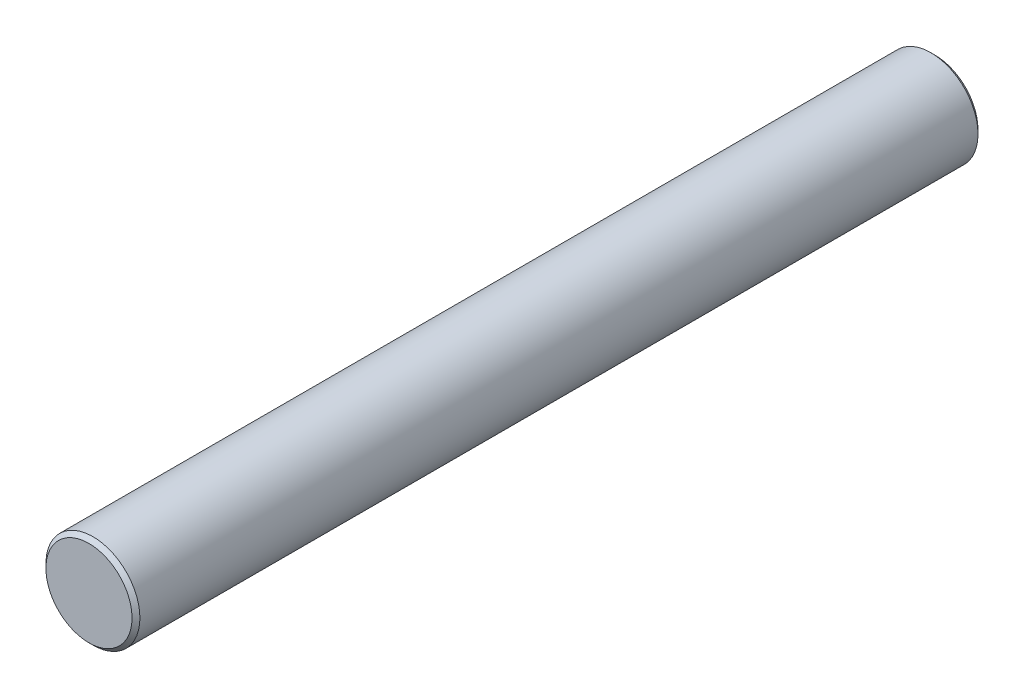
SolidWorks part; units mm, degrees
ref_plane "Front Plane" through (0, 0, 0) normal (0, 0, 1) x (1, 0, 0)
ref_plane "Top Plane" through (0, 0, 0) normal (0, 1, 0) x (1, 0, 0)
ref_plane "Right Plane" through (0, 0, 0) normal (1, 0, 0) x (0, 0, -1)
sketch "Sketch1" plane through (0, 0, 0) normal (0, 0, 1) x (1, 0, 0)
  circle A0 centre (0, 0) radius 4.7625
  dimension "D1" = 9.525
extrude "Boss-Extrude1" add sketch "Sketch1" along normal blind 85.725
chamfer "Chamfer1" distance 0.4 angle 45 2 edges at (4.7625, 0, 85.725) (4.7625, 0, 0)
